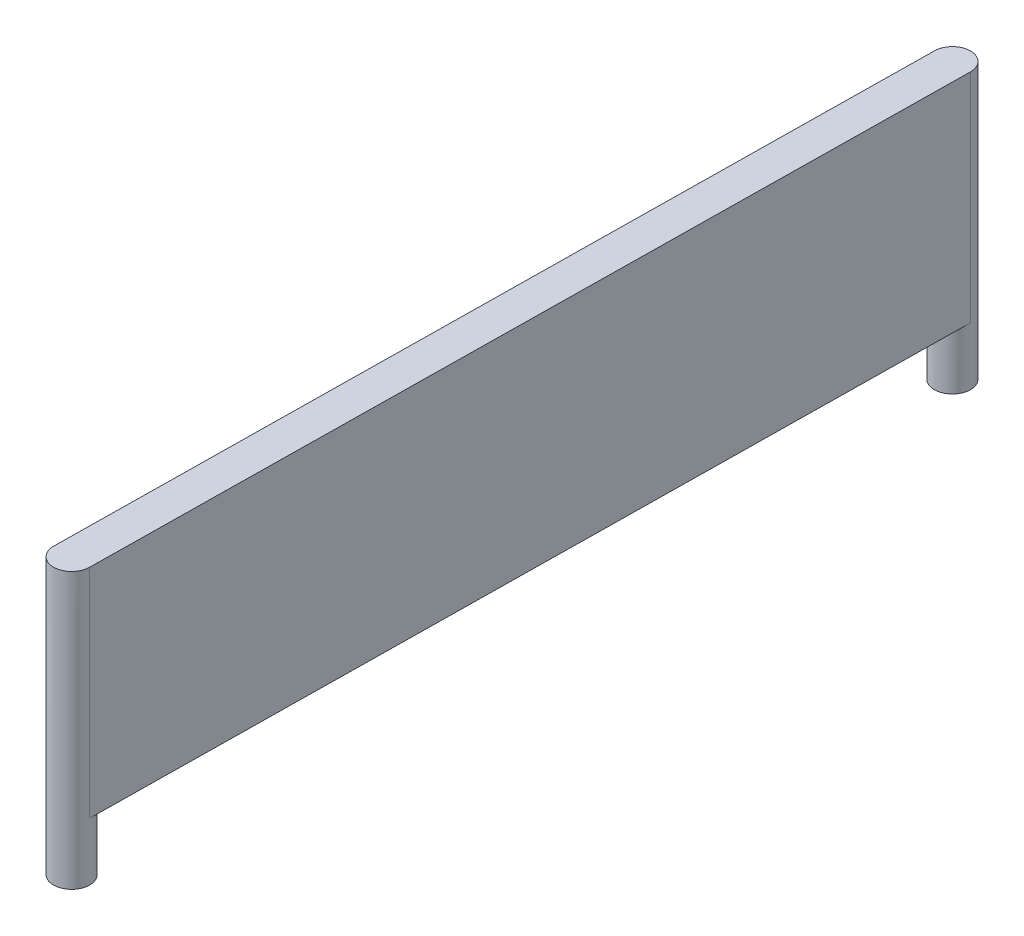
SolidWorks part; units mm, degrees
ref_plane "Front Plane" through (0, 0, 0) normal (0, 0, 1) x (1, 0, 0)
ref_plane "Top Plane" through (0, 0, 0) normal (0, 1, 0) x (1, 0, 0)
ref_plane "Right Plane" through (0, 0, 0) normal (1, 0, 0) x (0, 0, -1)
sketch "Sketch1" plane through (0, 0, 0) normal (0, 1, 0) x (1, 0, 0)
  line L0 (0, 0) -> (2.0026, 152.4) construction
  line L1 (-3.1747, 0.0417) -> (-1.1721, 152.4417)
  line L2 (3.1747, -0.0417) -> (5.1773, 152.3583)
  arc A0 (-3.1747, 0.0417) -> (3.1747, -0.0417) centre (0, 0) ccw
  arc A1 (5.1773, 152.3583) -> (-1.1721, 152.4417) centre (2.0026, 152.4) ccw
  point P3 (1.0013, 76.2)
  dimension "D2" = 3.175
  dimension "D1" = 152.4
extrude "Boss-Extrude1" add sketch "Sketch1" along normal blind 38.1
sketch "Sketch2" plane through (0, 0, 0) normal (0, -1, 0) x (-1, 0, 0)
  circle A0 centre (-2.0026, 152.4) radius 3.175
  circle A1 centre (0, 0) radius 3.175
extrude "Boss-Extrude2" add sketch "Sketch2" along normal blind 10.16
